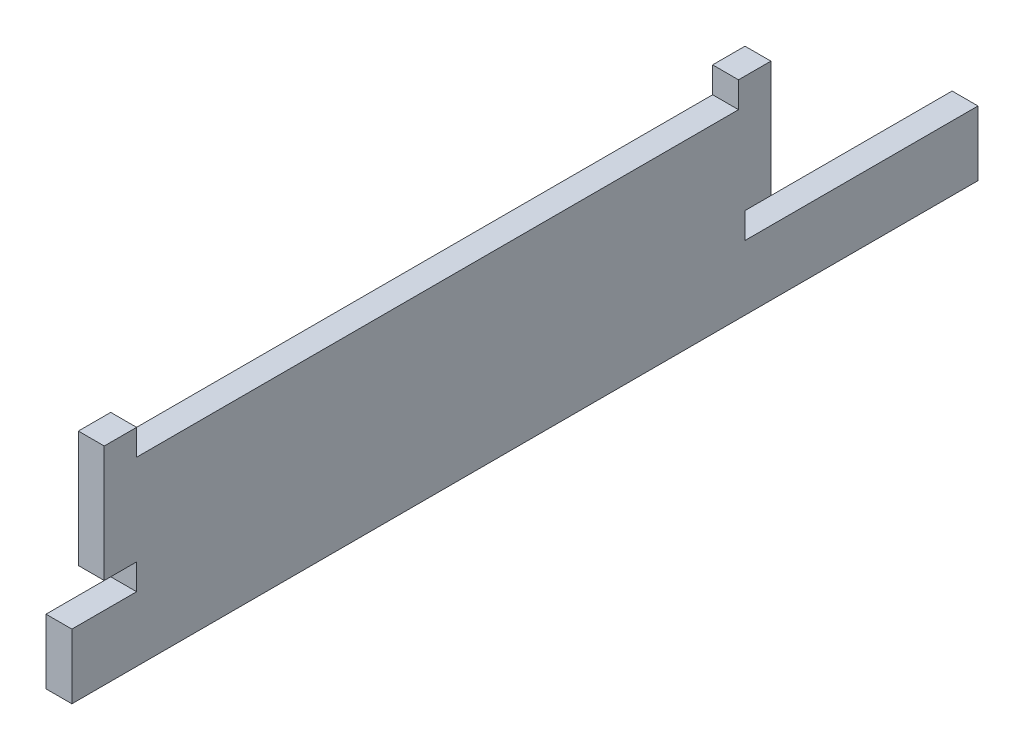
SolidWorks part; units mm, degrees
material "Beech"
ref_plane "Front Plane" through (0, 0, 0) normal (0, 0, 1) x (1, 0, 0)
ref_plane "Top Plane" through (0, 0, 0) normal (0, 1, 0) x (1, 0, 0)
ref_plane "Right Plane" through (0, 0, 0) normal (1, 0, 0) x (0, 0, -1)
sketch "Sketch1" plane through (0, 0, 0) normal (1, 0, 0) x (0, 0, -1)
  line L0 (-10.2358, 17.3984) -> (-10.2358, -0.6016)
  line L1 (-10.2358, -0.6016) -> (-5.2358, -0.6016)
  line L2 (-5.2358, -0.6016) -> (-5.2358, -4.6016)
  line L3 (-5.2358, -4.6016) -> (-15.2358, -4.6016)
  line L4 (-15.2358, -4.6016) -> (-15.2358, -14.6016)
  line L7 (87.7642, 13.3984) -> (-5.2358, 13.3984)
  line L8 (-5.2358, 13.3984) -> (-5.2358, 17.3984)
  line L9 (-5.2358, 17.3984) -> (-10.2358, 17.3984)
  line L10 (87.7642, 13.3984) -> (87.7642, 17.3984)
  line L11 (87.7642, 17.3984) -> (92.7642, 17.3984)
  line L12 (92.7642, 17.3984) -> (92.7642, -0.6016)
  line L13 (92.7642, -0.6016) -> (88.7642, -0.6016)
  line L14 (88.7642, -0.6016) -> (88.7642, -4.6016)
  line L15 (88.7642, -4.6016) -> (124.7642, -4.6016)
  line L16 (124.7642, -4.6016) -> (124.7642, -14.6016)
  line L17 (-15.2358, -14.6016) -> (124.7642, -14.6016)
  dimension "D1" = 4
  dimension "D2" = 5
  dimension "D3" = 5
  dimension "D4" = 18
  dimension "D5" = 10
  dimension "D6" = 10
  dimension "D7" = 93
  dimension "D8" = 5
  dimension "D9" = 4
  dimension "D10" = 140
extrude "Boss-Extrude1" add sketch "Sketch1" along normal blind 4
